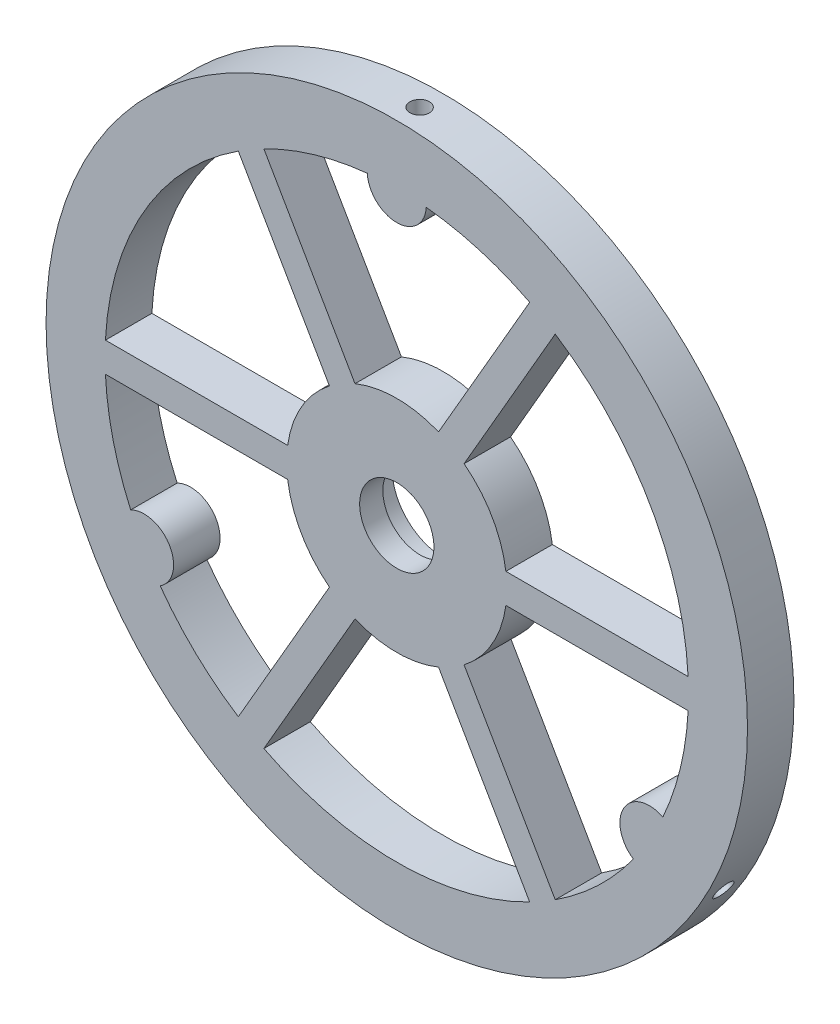
SolidWorks part; units mm, degrees
material "PET"
ref_plane "Front Plane" through (0, 0, 0) normal (0, 0, 1) x (1, 0, 0)
ref_plane "Top Plane" through (0, 0, 0) normal (0, 1, 0) x (1, 0, 0)
ref_plane "Right Plane" through (0, 0, 0) normal (1, 0, 0) x (0, 0, -1)
sketch "Sketch1" plane through (0, 0, 0) normal (0, 0, 1) x (1, 0, 0)
  circle A0 centre (0, 0) radius 75.5
  circle A1 centre (0, 0) radius 12.7
  dimension "D1" = 151
  dimension "D2" = 25.4
extrude "Boss-Extrude1" add sketch "Sketch1" along normal blind 10 contours A0
sketch "Sketch2" plane through (0, 0, 10) normal (0, 0, 1) x (1, 0, 0)
  circle A0 centre (0, 0) radius 11
  dimension "D1" = 22
extrude "Cut-Extrude1" cut sketch "Sketch2" along normal blind 5 from surface at -10 starting at face at (75.5, 0, 0)
sketch "Sketch3" plane through (0, 0, 5) normal (0, 0, -1) x (-1, 0, 0)
  circle A0 centre (0, 0) radius 8
  dimension "D1" = 16
extrude "Cut-Extrude2" cut sketch "Sketch3" against normal through all
ref_plane "Plane1" through (0, 75.5, 0) normal (0, 1, 0) x (1, 0, 0)
sketch "Sketch5" plane through (0, 75.5, 0) normal (0, 1, 0) x (1, 0, 0)
  line L0 (75.5, 0) -> (-75.5, 0) construction
  circle A0 centre (0, -5.08) radius 2.0828
  dimension "D2" = 4.1656
  dimension "D1" = 5.08
extrude "Cut-Extrude4" cut sketch "Sketch5" against normal blind 12.7
pattern_circular "CirPattern2" count 3 over 360 about axis through (0, 0, 0) along (0, 0, 1) of "Cut-Extrude4"
sketch "Sketch6" plane through (0, 0, 0) normal (0, 0, -1) x (-1, 0, 0)
  line L0 (0, 0) -> (0, 75.5) construction
  line L1 (0, 0) -> (-37.75, 65.3849)
  line L2 (0, 0) -> (37.75, 65.3849)
  line L3 (-9.4496, 10.0172) -> (-34.1496, 52.7989)
  line L4 (-9.4496, 10.0172) -> (-3.9504, 13.1922)
  line L5 (-34.1496, 52.7989) -> (-28.6504, 55.9739)
  line L6 (-3.9504, 13.1922) -> (-28.6504, 55.9739)
  line L7 (-9.4496, 10.0172) -> (-28.6504, 55.9739) construction
  line L8 (-34.1496, 52.7989) -> (-3.9504, 13.1922) construction
  line L9 (3.9504, 13.1922) -> (28.6504, 55.9739)
  line L10 (3.9504, 13.1922) -> (9.4496, 10.0172)
  line L11 (28.6504, 55.9739) -> (34.1496, 52.7989)
  line L12 (9.4496, 10.0172) -> (34.1496, 52.7989)
  line L13 (3.9504, 13.1922) -> (34.1496, 52.7989) construction
  line L14 (28.6504, 55.9739) -> (9.4496, 10.0172) construction
  circle A0 centre (0, 0) radius 23.7
  circle A1 centre (0, 0) radius 56.45
  circle A2 centre (0, 0) radius 75.5 construction
  circle A3 centre (0, 0) radius 11 construction
  circle A4 centre (0, 0) radius 62.8
  circle A5 centre (0, 62.8) radius 6.35
  point P9 (-31.4, 54.3864)
  point P13 (-19.05, 32.9956)
  point P15 (19.05, 32.9956)
  point P16 (31.4, 54.3864)
  dimension "D1" = 19.05
  dimension "D2" = 12.7
  dimension "D3" = 12.7
  dimension "D4" = 30
  dimension "D5" = 30
  dimension "D6" = 6.35
extrude "Cut-Extrude5" cut sketch "Sketch6" against normal through all contours L9 A1 L6 A0 | A5 A1 L9 A4 | A5 A4 L6 A1
pattern_circular "CirPattern3" count 6 over 360 about axis through (0, 0, 0) along (0, 0, 1) of "Cut-Extrude5"
sketch "Sketch8" plane through (0, 0, 0) normal (0, 0, -1) x (-1, 0, 0)
  circle A0 centre (0, 0) radius 62.8
  arc A1 (-57.2793, 25.7473) -> (-50.9374, 36.7317) centre (-54.3864, 31.4) ccw construction
  arc A2 (-57.2793, 25.7473) -> (-50.9374, 36.7317) centre (-54.3864, 31.4) ccw
  arc M31 (-57.2793, 25.7473) -> (-50.9374, 36.7317) centre (-54.3864, 31.4) ccw
extrude "Cut-Extrude6" cut sketch "Sketch8" against normal through all contours A0 M31
pattern_circular "CirPattern4" count 3 over 360 about axis through (0, 0, 5) along (0, 0, -1) of "Cut-Extrude6"
